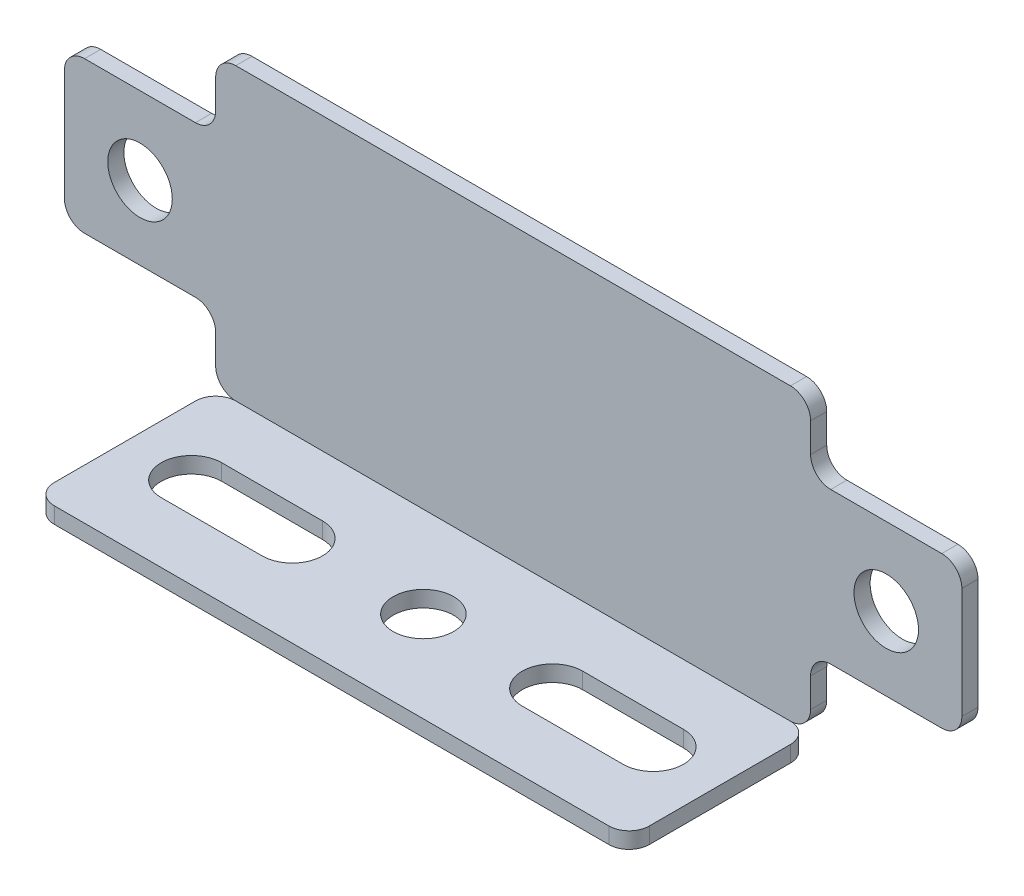
SolidWorks part; units mm, degrees
ref_plane "Plan de face" through (0, 0, 0) normal (0, 0, 1) x (1, 0, 0)
ref_plane "Plan de dessus" through (0, 0, 0) normal (0, 1, 0) x (1, 0, 0)
ref_plane "Plan de droite" through (0, 0, 0) normal (1, 0, 0) x (0, 0, -1)
sketch "Esquisse1" plane through (0, 0, 0) normal (0, 0, 1) x (1, 0, 0)
  line L0 (0, 0) -> (0, 7.5)
  line L1 (0, 7.5) -> (7.5, 7.5)
  line L2 (7.5, 7.5) -> (7.5, 10.95)
  line L3 (7.5, 10.95) -> (37, 10.95)
  line L4 (37, 10.95) -> (37, 7.5)
  line L5 (37, 7.5) -> (44.5, 7.5)
  line L6 (44.5, 7.5) -> (44.5, 0)
  line L7 (44.5, 0) -> (37, 0)
  line L8 (37, 0) -> (37, -3.45)
  line L9 (37, -3.45) -> (7.5, -3.45)
  line L10 (7.5, -3.45) -> (7.5, 0)
  line L11 (7.5, 0) -> (0, 0)
  point P13 (0, 0)
  dimension "D1" = 44.5
  dimension "D2" = 14.4
  dimension "D3" = 7.5
  dimension "D4" = 7.5
  dimension "D5" = 3.45
  dimension "D6" = 29.5
  dimension "D7" = 29.5
  dimension "D8" = 7.5
extrude "Boss.-Extru.1" add sketch "Esquisse1" along normal blind 0.8
fillet "Congé2" radius 1 12 edges at (37, 7.5, 0.4) (37, 10.95, 0.4) (44.5, 7.5, 0.4) (44.5, 0, 0.4) (37, 0, 0.4) (37, -3.45, 0.4) (7.5, -3.45, 0.4) (7.5, 0, 0.4) (0, 0, 0.4) (0, 7.5, 0.4) (7.5, 7.5, 0.4) (7.5, 10.95, 0.4)
hole_wizard "Diamètre du perçage Ø3.2 (3.2)1" positions "Esquisse2" profile "Esquisse3" hole size "Ø3.2" standard "ISO"
sketch "Esquisse2" plane through (0, 0, 0.8) normal (0, 0, 1) x (1, 0, 0)
  line L1 (8.5, -3.45) -> (36, -3.45) construction
  line L2 (0, 6.5) -> (0, 1) construction
  line L6 (38, 0) -> (43.5, 0) construction
  point P0 (3.75, 3.65)
  point P2 (40.75, 3.65)
  point P17 (0, 0)
  dimension "D1" = 37
  dimension "D2" = 7.1
  dimension "D3" = 3.75
  dimension "D5" = 3.65
sketch "Esquisse3" plane through (3.75, 3.65, 0.8) normal (1, 0, 0) x (0, -1, 0)
  line L0 (0, 0) -> (0, 8.9614)
  line L1 (0, 8.9614) -> (1.6, 8)
  line L2 (1.6, 8) -> (1.6, 0)
  line L5 (1.6, 0) -> (0, 0)
  line L10 (0, 8.9614) -> (-1.6, 8) construction
  line L11 (0, -6.35) -> (0, 107.95) construction
  dimension "Diamètre du perçage" = 3.2
  dimension "Profondeur du perçage" = 8
  dimension "Angle de pointe" = 118
sketch "Esquisse4" plane through (0, 0, 0.8) normal (0, 0, 1) x (1, 0, 0)
  line L0 (8.5, -3.45) -> (36, -3.45) construction
  line L1 (7.5, -3.45) -> (37, -3.45)
  line L2 (7.5, -3.45) -> (7.5, -4.25)
  line L3 (7.5, -4.25) -> (37, -4.25)
  line L4 (37, -3.45) -> (37, -4.25)
  point P6 (0, 0)
  point P7 (0, 0)
  point P9 (0, 0)
  dimension "D1" = 0.8
  dimension "D2" = 0
extrude "Boss.-Extru.2" add sketch "Esquisse4" along normal blind 9 separate body
fillet "Congé3" radius 1 4 edges at (37, -3.85, 0.8) (37, -3.85, 9.8) (7.5, -3.85, 9.8) (7.5, -3.85, 0.8)
sketch "Esquisse5" plane through (0, -3.45, 0) normal (0, 1, 0) x (1, 0, 0)
  line L0 (7.5, -5.3) -> (37, -5.3) construction
  line L1 (7.5, -8.8) -> (7.5, -1.8) construction
  line L2 (37, -8.8) -> (37, -1.8) construction
  line L3 (10.8, -5.3) -> (15.8, -5.3) construction
  line L4 (10.8, -3.8) -> (15.8, -3.8)
  line L5 (10.8, -6.8) -> (15.8, -6.8)
  line L6 (28.7, -5.3) -> (33.7, -5.3) construction
  line L7 (28.7, -3.8) -> (33.7, -3.8)
  line L8 (28.7, -6.8) -> (33.7, -6.8)
  arc A0 (10.8, -3.8) -> (10.8, -6.8) centre (10.8, -5.3) ccw
  arc A1 (15.8, -6.8) -> (15.8, -3.8) centre (15.8, -5.3) ccw
  arc A2 (28.7, -3.8) -> (28.7, -6.8) centre (28.7, -5.3) ccw
  arc A3 (33.7, -6.8) -> (33.7, -3.8) centre (33.7, -5.3) ccw
  circle A4 centre (22.3, -5.3) radius 1.5
  point P8 (13.3, -5.3)
  point P13 (31.2, -5.3)
  dimension "D8" = 3
  dimension "D1" = 3.3
  dimension "D2" = 3.3
  dimension "D3" = 5
  dimension "D4" = 5
  dimension "D5" = 3
  dimension "D6" = 3
  dimension "D7" = 6.5
extrude "Enlèv. mat.-Extru.1" cut sketch "Esquisse5" against normal blind 9
